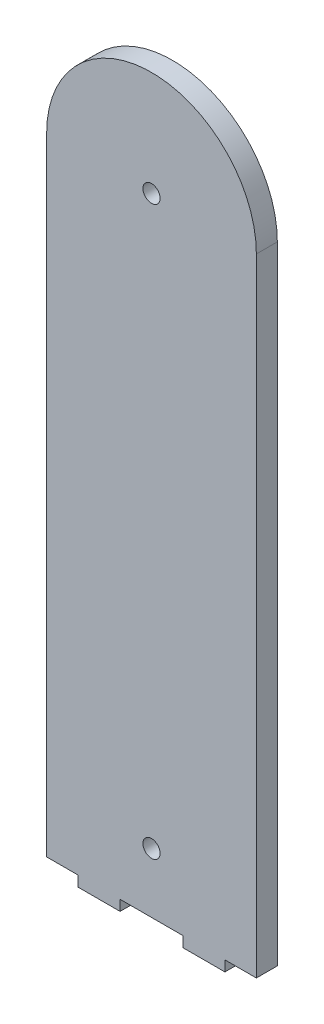
SolidWorks part; units mm, degrees
ref_plane "前基準面" through (0, 0, 0) normal (0, 0, 1) x (1, 0, 0)
ref_plane "上基準面" through (0, 0, 0) normal (0, 1, 0) x (1, 0, 0)
ref_plane "右基準面" through (0, 0, 0) normal (1, 0, 0) x (0, 0, -1)
sketch "草圖1" plane through (0, 0, 0) normal (0, 0, 1) x (1, 0, 0)
  line L0 (-50, 0) -> (-35, 0)
  line L1 (-50, 0) -> (-50, 299)
  line L2 (50, 0) -> (50, 299)
  line L3 (0, 299.9843) -> (0, -20.7711) construction
  line L5 (-35, 0) -> (-35, -5)
  line L6 (-35, -5) -> (-15, -5)
  line L7 (-15, 0) -> (-15, -5)
  line L12 (35, -5) -> (15, -5)
  line L13 (15, 0) -> (15, -5)
  line L15 (35, 0) -> (35, -5)
  line L16 (-15, 0) -> (15, 0)
  line L17 (35, 0) -> (50, 0)
  line L18 (-21.8, 299) -> (-15, 28.5) construction
  line L19 (28.5, 0) -> (-28.5, 0) construction
  line L20 (28.5, 0) -> (28.5, 57) construction
  line L21 (28.5, 57) -> (-28.5, 57) construction
  line L22 (-28.5, 0) -> (-28.5, 57) construction
  line L23 (21.8, 299) -> (15, 28.5) construction
  arc A0 (-50, 299) -> (50, 299) centre (0, 299) cw
  circle A1 centre (0, 299) radius 4.1
  circle A2 centre (0, 28.5) radius 4.1
  circle A3 centre (0, 28.5) radius 15 construction
  circle A4 centre (0, 299) radius 21.8 construction
  point P17 (0, 57)
  point P25 (-28.5, 28.5)
  dimension "D2" = 8.2
  dimension "D8" = 8.2
  dimension "D9" = 43.6
  dimension "D11" = 30
  dimension "D1" = 100
  dimension "D3" = 5
  dimension "D4" = 20
  dimension "D5" = 15
  dimension "D6" = 57
  dimension "D7" = 57
  dimension "D10" = 270.5
extrude "填料-伸長1" add sketch "草圖1" against normal blind 10
